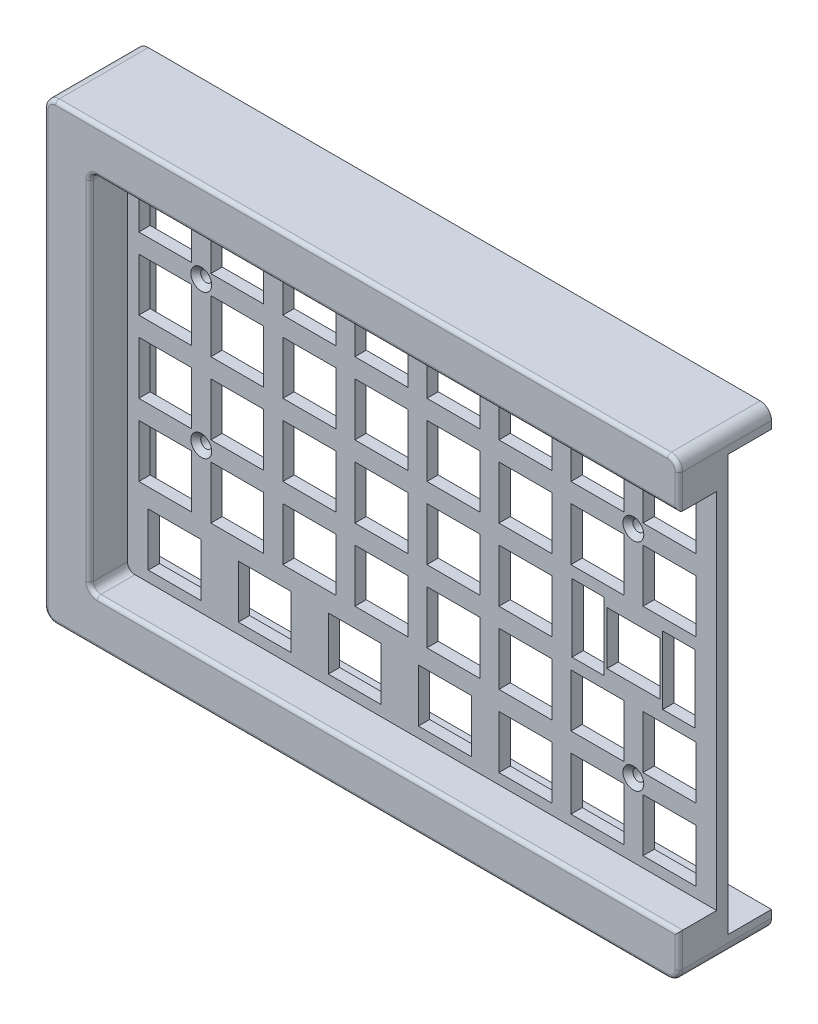
SolidWorks part; units mm, degrees
ref_plane "Front Plane" through (0, 0, 0) normal (0, 0, 1) x (1, 0, 0)
ref_plane "Top Plane" through (0, 0, 0) normal (0, 1, 0) x (1, 0, 0)
ref_plane "Right Plane" through (0, 0, 0) normal (1, 0, 0) x (0, 0, -1)
sketch "Sketch1" plane through (0, 0, 0) normal (0, 0, 1) x (1, 0, 0)
  line L1 (-80.925, -60) -> (80.925, -60)
  line L2 (-83.925, -57) -> (-83.925, 57)
  line L3 (-80.925, 60) -> (80.925, 60)
  line L4 (83.925, -57) -> (83.925, 57)
  line L5 (-83.925, -60) -> (83.925, 60) construction
  line L6 (-83.925, 60) -> (83.925, -60) construction
  arc A0 (80.925, -60) -> (83.925, -57) centre (80.925, -57) ccw
  arc A1 (80.925, 60) -> (83.925, 57) centre (80.925, 57) cw
  arc A2 (-83.925, 57) -> (-80.925, 60) centre (-80.925, 57) cw
  arc A3 (-80.925, -60) -> (-83.925, -57) centre (-80.925, -57) cw
  point P0 (0, 0)
  dimension "D3" = 3
  dimension "D1" = 167.85
  dimension "D2" = 120
extrude "Main Extrusion" add sketch "Sketch1" along normal blind 24.5
sketch "Sketch3" plane through (0, 0, 24.5) normal (0, 0, 1) x (1, 0, 0)
  line L0 (-83.925, 57) -> (-83.925, -57) construction
  line L1 (-69.925, 48) -> (82.025, 48)
  line L2 (-71.925, 46) -> (-71.925, -46)
  line L3 (-69.925, -48) -> (82.025, -48)
  line L4 (83.925, 46) -> (83.925, -46)
  line L5 (-71.925, 48) -> (83.925, -48) construction
  line L6 (-71.925, -48) -> (83.925, 48) construction
  line L7 (-80.925, -60) -> (80.925, -60) construction
  line L8 (83.925, -46) -> (83.925, -48)
  line L9 (80.925, 60) -> (-80.925, 60) construction
  line L10 (83.925, -48) -> (82.025, -48)
  line L11 (83.925, -57) -> (83.925, 57) construction
  line L12 (82.025, 48) -> (83.925, 48)
  line L13 (83.925, 48) -> (83.925, 46)
  arc A2 (-71.925, -46) -> (-69.925, -48) centre (-69.925, -46) ccw
  arc A3 (-69.925, 48) -> (-71.925, 46) centre (-69.925, 46) ccw
  point P0 (6, 0)
  dimension "D6" = 2
  dimension "D1" = 12
  dimension "D2" = 0
  dimension "D3" = 12
  dimension "D4" = 12
extrude "Front Cave" cut sketch "Sketch3" against normal blind 10
sketch "Sketch2" plane through (0, 0, 14.5) normal (0, 0, 1) x (1, 0, 0)
  line L1 (-68.925, 31) -> (-54.925, 31)
  line L2 (-68.925, 31) -> (-68.925, 45)
  line L3 (-68.925, 45) -> (-54.925, 45)
  line L4 (-54.925, 31) -> (-54.925, 45)
  line L5 (-68.925, 31) -> (-54.925, 45) construction
  line L6 (-68.925, 45) -> (-54.925, 31) construction
  line L7 (-49.875, 31) -> (-49.875, 45)
  line L8 (-49.875, 31) -> (-35.875, 31)
  line L9 (-35.875, 31) -> (-35.875, 45)
  line L10 (-49.875, 45) -> (-35.875, 45)
  line L11 (-30.825, 31) -> (-30.825, 45)
  line L12 (-30.825, 31) -> (-16.825, 31)
  line L13 (-16.825, 31) -> (-16.825, 45)
  line L14 (-30.825, 45) -> (-16.825, 45)
  line L15 (-11.775, 31) -> (-11.775, 45)
  line L16 (-11.775, 31) -> (2.225, 31)
  line L17 (2.225, 31) -> (2.225, 45)
  line L18 (-11.775, 45) -> (2.225, 45)
  line L19 (7.275, 31) -> (7.275, 45)
  line L20 (7.275, 31) -> (21.275, 31)
  line L21 (21.275, 31) -> (21.275, 45)
  line L22 (7.275, 45) -> (21.275, 45)
  line L23 (26.325, 31) -> (26.325, 45)
  line L24 (26.325, 31) -> (40.325, 31)
  line L25 (40.325, 31) -> (40.325, 45)
  line L26 (26.325, 45) -> (40.325, 45)
  line L27 (45.375, 31) -> (45.375, 45)
  line L28 (45.375, 31) -> (59.375, 31)
  line L100 (-42.613, -31.2) -> (-42.613, -45.2)
  line L101 (-66.425, -31.2) -> (-52.425, -31.2)
  line L102 (-66.425, -31.2) -> (-66.425, -45.2)
  line L103 (-66.425, -45.2) -> (-52.425, -45.2)
  line L104 (-52.425, -31.2) -> (-52.425, -45.2)
  line L105 (-66.425, -31.2) -> (-52.425, -45.2) construction
  line L106 (-66.425, -45.2) -> (-52.425, -31.2) construction
  line L107 (-42.613, -31.2) -> (-28.613, -31.2)
  line L108 (-28.613, -31.2) -> (-28.613, -45.2)
  line L109 (-42.613, -45.2) -> (-28.613, -45.2)
  line L110 (-18.801, -31.2) -> (-18.801, -45.2)
  line L111 (-18.801, -31.2) -> (-4.801, -31.2)
  line L112 (-4.801, -31.2) -> (-4.801, -45.2)
  line L113 (-18.801, -45.2) -> (-4.801, -45.2)
  line L119 (5.011, -31.2) -> (5.011, -45.2)
  line L120 (5.011, -31.2) -> (19.011, -31.2)
  line L125 (80.925, 60) -> (-80.925, 60) construction
  line L126 (-83.925, 57) -> (-83.925, -57) construction
  line L127 (59.375, 31) -> (59.375, 45)
  line L132 (19.011, -31.2) -> (19.011, -45.2)
  line L133 (5.011, -45.2) -> (19.011, -45.2)
  line L134 (69.65, -9.1) -> (78.15, -9.1)
  line L135 (69.65, -9.1) -> (69.65, 8.9)
  line L136 (69.65, 8.9) -> (78.15, 8.9)
  line L137 (78.15, -9.1) -> (78.15, 8.9)
  line L138 (69.65, -9.1) -> (78.15, 8.9) construction
  line L139 (69.65, 8.9) -> (78.15, -9.1) construction
  line L140 (45.375, 45) -> (59.375, 45)
  line L141 (64.425, 31) -> (64.425, 45)
  line L142 (64.425, 31) -> (78.425, 31)
  line L143 (78.425, 31) -> (78.425, 45)
  line L144 (64.425, 45) -> (78.425, 45)
  line L145 (-68.925, 11.95) -> (-68.925, 25.95)
  line L146 (-68.925, 11.95) -> (-54.925, 11.95)
  line L147 (-54.925, 11.95) -> (-54.925, 25.95)
  line L148 (-68.925, 25.95) -> (-54.925, 25.95)
  line L149 (-49.875, 11.95) -> (-49.875, 25.95)
  line L150 (-49.875, 25.95) -> (-35.875, 25.95)
  line L151 (-35.875, 11.95) -> (-35.875, 25.95)
  line L152 (-49.875, 11.95) -> (-35.875, 11.95)
  line L153 (-30.825, 11.95) -> (-30.825, 25.95)
  line L154 (-30.825, 25.95) -> (-16.825, 25.95)
  line L155 (-16.825, 11.95) -> (-16.825, 25.95)
  line L156 (-30.825, 11.95) -> (-16.825, 11.95)
  line L157 (-11.775, 11.95) -> (-11.775, 25.95)
  line L158 (-11.775, 25.95) -> (2.225, 25.95)
  line L159 (2.225, 11.95) -> (2.225, 25.95)
  line L160 (-11.775, 11.95) -> (2.225, 11.95)
  line L161 (7.275, 11.95) -> (7.275, 25.95)
  line L162 (7.275, 25.95) -> (21.275, 25.95)
  line L163 (21.275, 11.95) -> (21.275, 25.95)
  line L164 (7.275, 11.95) -> (21.275, 11.95)
  line L165 (26.325, 11.95) -> (26.325, 25.95)
  line L166 (26.325, 25.95) -> (40.325, 25.95)
  line L167 (40.325, 11.95) -> (40.325, 25.95)
  line L168 (26.325, 11.95) -> (40.325, 11.95)
  line L169 (45.375, 11.95) -> (45.375, 25.95)
  line L170 (45.375, 25.95) -> (59.375, 25.95)
  line L171 (59.375, 11.95) -> (59.375, 25.95)
  line L172 (45.375, 11.95) -> (59.375, 11.95)
  line L173 (64.425, 11.95) -> (64.425, 25.95)
  line L174 (64.425, 25.95) -> (78.425, 25.95)
  line L175 (78.425, 11.95) -> (78.425, 25.95)
  line L176 (64.425, 11.95) -> (78.425, 11.95)
  line L177 (-68.925, -7.1) -> (-68.925, 6.9)
  line L178 (-68.925, -7.1) -> (-54.925, -7.1)
  line L179 (-54.925, -7.1) -> (-54.925, 6.9)
  line L180 (-68.925, 6.9) -> (-54.925, 6.9)
  line L181 (-49.875, -7.1) -> (-49.875, 6.9)
  line L182 (-49.875, 6.9) -> (-35.875, 6.9)
  line L183 (-35.875, -7.1) -> (-35.875, 6.9)
  line L184 (-49.875, -7.1) -> (-35.875, -7.1)
  line L185 (-30.825, -7.1) -> (-30.825, 6.9)
  line L186 (-30.825, 6.9) -> (-16.825, 6.9)
  line L187 (-16.825, -7.1) -> (-16.825, 6.9)
  line L188 (-30.825, -7.1) -> (-16.825, -7.1)
  line L189 (-11.775, -7.1) -> (-11.775, 6.9)
  line L190 (-11.775, 6.9) -> (2.225, 6.9)
  line L191 (2.225, -7.1) -> (2.225, 6.9)
  line L192 (-11.775, -7.1) -> (2.225, -7.1)
  line L193 (7.275, -7.1) -> (7.275, 6.9)
  line L194 (7.275, 6.9) -> (21.275, 6.9)
  line L195 (21.275, -7.1) -> (21.275, 6.9)
  line L196 (7.275, -7.1) -> (21.275, -7.1)
  line L197 (26.325, -7.1) -> (26.325, 6.9)
  line L198 (26.325, 6.9) -> (40.325, 6.9)
  line L199 (40.325, -7.1) -> (40.325, 6.9)
  line L200 (26.325, -7.1) -> (40.325, -7.1)
  line L209 (-68.925, -26.15) -> (-68.925, -12.15)
  line L210 (-68.925, -26.15) -> (-54.925, -26.15)
  line L211 (-54.925, -26.15) -> (-54.925, -12.15)
  line L212 (-68.925, -12.15) -> (-54.925, -12.15)
  line L213 (-49.875, -26.15) -> (-49.875, -12.15)
  line L214 (-49.875, -12.15) -> (-35.875, -12.15)
  line L215 (-35.875, -26.15) -> (-35.875, -12.15)
  line L216 (-49.875, -26.15) -> (-35.875, -26.15)
  line L217 (-30.825, -26.15) -> (-30.825, -12.15)
  line L218 (-30.825, -12.15) -> (-16.825, -12.15)
  line L219 (-16.825, -26.15) -> (-16.825, -12.15)
  line L220 (-30.825, -26.15) -> (-16.825, -26.15)
  line L221 (-11.775, -26.15) -> (-11.775, -12.15)
  line L222 (-11.775, -12.15) -> (2.225, -12.15)
  line L223 (2.225, -26.15) -> (2.225, -12.15)
  line L224 (-11.775, -26.15) -> (2.225, -26.15)
  line L225 (7.275, -26.15) -> (7.275, -12.15)
  line L226 (7.275, -12.15) -> (21.275, -12.15)
  line L227 (21.275, -26.15) -> (21.275, -12.15)
  line L228 (7.275, -26.15) -> (21.275, -26.15)
  line L229 (26.325, -26.15) -> (26.325, -12.15)
  line L230 (26.325, -12.15) -> (40.325, -12.15)
  line L231 (40.325, -26.15) -> (40.325, -12.15)
  line L232 (26.325, -26.15) -> (40.325, -26.15)
  line L233 (45.375, -26.15) -> (45.375, -12.15)
  line L234 (45.375, -12.15) -> (59.375, -12.15)
  line L235 (59.375, -26.15) -> (59.375, -12.15)
  line L236 (45.375, -26.15) -> (59.375, -26.15)
  line L237 (64.425, -26.15) -> (64.425, -12.15)
  line L238 (64.425, -12.15) -> (78.425, -12.15)
  line L239 (78.425, -26.15) -> (78.425, -12.15)
  line L240 (64.425, -26.15) -> (78.425, -26.15)
  line L241 (45.375, -7.1) -> (45.375, 6.9) [skipped]
  line L242 (45.375, 6.9) -> (59.375, 6.9) [skipped]
  line L243 (59.375, -7.1) -> (59.375, 6.9) [skipped]
  line L244 (45.375, -7.1) -> (59.375, -7.1) [skipped]
  line L245 (64.425, -7.1) -> (64.425, 6.9) [skipped]
  line L246 (64.425, 6.9) -> (78.425, 6.9) [skipped]
  line L247 (78.425, -7.1) -> (78.425, 6.9) [skipped]
  line L248 (64.425, -7.1) -> (78.425, -7.1) [skipped]
  line L249 (61.9, 6.9) -> (61.9, -7.1) construction
  line L250 (54.9, -7.1) -> (68.9, -7.1)
  line L251 (54.9, -7.1) -> (54.9, 6.9)
  line L252 (54.9, 6.9) -> (68.9, 6.9)
  line L253 (68.9, -7.1) -> (68.9, 6.9)
  line L254 (54.9, -7.1) -> (68.9, 6.9) construction
  line L255 (54.9, 6.9) -> (68.9, -7.1) construction
  line L256 (54.15, 8.9) -> (45.65, 8.9)
  line L257 (45.65, -9.1) -> (45.65, 8.9)
  line L258 (54.15, -9.1) -> (45.65, -9.1)
  line L259 (54.15, -9.1) -> (54.15, 8.9)
  line L260 (26.325, -45.2) -> (26.325, -31.2)
  line L261 (26.325, -31.2) -> (40.325, -31.2)
  line L262 (40.325, -45.2) -> (40.325, -31.2)
  line L263 (26.325, -45.2) -> (40.325, -45.2)
  line L264 (45.375, -45.2) -> (45.375, -31.2)
  line L265 (45.375, -31.2) -> (59.375, -31.2)
  line L266 (59.375, -45.2) -> (59.375, -31.2)
  line L267 (45.375, -45.2) -> (59.375, -45.2)
  line L268 (64.425, -45.2) -> (64.425, -31.2)
  line L269 (64.425, -31.2) -> (78.425, -31.2)
  line L270 (78.425, -45.2) -> (78.425, -31.2)
  line L271 (64.425, -45.2) -> (78.425, -45.2)
  line L273 (83.925, -48) -> (83.925, 48) construction
  point P0 (-61.925, 38)
  point P29 (-59.425, -38.2)
  point P30 (61.9, -0.1)
  point P141 (73.9, -0.1)
  dimension "D22" = 5.05
  dimension "D1" = 14
  dimension "D2" = 14
  dimension "D3" = 8
  dimension "D5" = 15
  dimension "D6" = 5.05
  dimension "D7" = 4
  dimension "D8" = 5.05
  dimension "D10" = 14
  dimension "D11" = 14
  dimension "D12" = 14
  dimension "D13" = 5.5
  dimension "D14" = 14
  dimension "D16" = 9.812
  dimension "D17" = 5.05
  dimension "D18" = 2
  dimension "D19" = 5.05
  dimension "D20" = 14.575
  dimension "D21" = 17.5
  dimension "D23" = 12
  dimension "D44" = 8.5
  dimension "D45" = 18
  dimension "D9" = 3
  dimension "D15" = 4
extrude "Key Cutouts" cut sketch "Sketch2" against normal blind 3
hole_wizard "CSK for M2.5 Countersunk Flat Head Screw1" positions "3DSketch1" profile "Sketch5" countersink size "M2.5" standard "ISO" end condition through all
sketch3d "3DSketch1"
  line L2 (-68.925, 31, 14.5) -> (-54.925, 31, 14.5) construction
  line L9 (-49.875, 25.95, 14.5) -> (-49.875, 11.95, 14.5) construction
  line L14 (59.375, -31.2, 14.5) -> (45.375, -31.2, 14.5) construction
  line L15 (64.425, -31.2, 14.5) -> (64.425, -45.2, 14.5) construction
  line L16 (-54.925, -7.1, 14.5) -> (-54.925, 6.9, 14.5) construction
  line L17 (-49.875, -7.1, 14.5) -> (-35.875, -7.1, 14.5) construction
  line L18 (64.425, 31, 14.5) -> (78.425, 31, 14.5) construction
  line L19 (64.425, 25.95, 14.5) -> (64.425, 11.95, 14.5) construction
  point P0 (-52.4, 28.475, 14.5)
  point P4 (61.895, -28.67, 14.5)
  point P6 (-52.4, -9.625, 14.5)
  point P64 (61.895, 28.47, 14.5)
  dimension "D1" = 2.525
  dimension "D2" = 2.525
  dimension "D3" = 2.525
  dimension "D4" = 2.525
  dimension "D5" = 2.53
  dimension "D6" = 2.53
  dimension "D7" = 2.53
  dimension "D8" = 2.53
sketch "Sketch5" plane through (-52.4, 28.475, 14.5) normal (1, 0, 0) x (0, -1, 0)
  line L0 (0, 0) -> (0, 14.5)
  line L1 (0, 14.5) -> (1.45, 14.5)
  line L2 (1.45, 14.5) -> (1.45, 1.3)
  line L3 (1.45, 1.3) -> (2.75, 0)
  line L5 (2.75, 0) -> (0, 0)
  line L6 (-1.45, 1.3) -> (-2.75, 0) construction
  line L11 (0, -6.35) -> (0, 107.95) construction
  dimension "Thru Hole Dia." = 2.9
  dimension "Thru Hole Depth" = 14.5
  dimension "Near C'Sink Dia." = 5.5
  dimension "Near C'Sink Angle" = 90
sketch "Sketch4" plane through (0, 0, 0) normal (0, 0, 1) x (1, 0, 0)
  line L5 (83.925, -57) -> (83.925, 57) construction
  line L6 (83.925, 55) -> (-78.925, 55)
  line L12 (83.925, 55) -> (83.925, -55)
  line L13 (83.925, -55) -> (-78.925, -55)
  line L14 (-78.925, 55) -> (-78.925, -55)
  line L15 (80.925, 60) -> (-80.925, 60) construction
  line L16 (-80.925, -60) -> (80.925, -60) construction
  line L17 (-83.925, 57) -> (-83.925, -57) construction
  dimension "D1" = 5
  dimension "D2" = 5
  dimension "D3" = 5
extrude "Cut-Extrude1" cut sketch "Sketch4" along normal up to surface (11.5 mm away) contours L14 L13 L12 L6 up to face at (-61.925, 18.95, 11.5)
sketch "Sketch7" plane through (-83.925, 0, 0) normal (-1, 0, 0) x (0, 0, 1)
  line L0 (0, 40) -> (7, 32)
  line L1 (0, 57) -> (0, -57) construction
  line L2 (7, 32) -> (7, -60)
  line L3 (7, -60) -> (0, -60)
  line L4 (0, -60) -> (0, 40)
  line L5 (24.5, 57) -> (0, 57) construction
  line L7 (24.5, -60) -> (0, -60) construction
  dimension "D1" = 17
  dimension "D2" = 25
  dimension "D5" = 7
sketch "Sketch8" plane through (0, -60, 0) normal (0, -1, 0) x (1, 0, 0)
  line L0 (-83.925, 0) -> (-83.925, 7)
  line L1 (-80.925, 0) -> (80.925, 0) construction
  line L2 (-83.925, 7) -> (55.925, 7)
  line L3 (55.925, 7) -> (63.925, 0)
  line L4 (63.925, 0) -> (-83.925, 0)
  line L6 (80.925, 24.5) -> (80.925, 0) construction
  line L7 (-83.925, 24.5) -> (-83.925, 0) construction
  dimension "D3" = 17
  dimension "D4" = 25
  dimension "D5" = 7
extrude "Cut-Extrude3" cut sketch "Sketch7" against normal blind 2.5
extrude "Cut-Extrude4" cut sketch "Sketch8" against normal blind 2.5
fillet "Fillet1" radius 1 15 edges at (-83.925, 0, 24.5) (-83.0463, 59.1213, 24.5) (0, 60, 24.5) (83.0463, 59.1213, 24.5) (83.925, 52.5, 24.5) (83.925, -52.5, 24.5) (83.0463, -59.1213, 24.5) (0, -60, 24.5) (-83.0463, -59.1213, 24.5) (7, -48, 24.5) (7, 48, 24.5) (-71.3392, 47.4142, 24.5) (-71.925, 0, 24.5) (-71.3392, -47.4142, 24.5) (-81.425, -57.5, 3.5)
sketch "Sketch10" plane through (0, 0, 11.5) normal (0, 0, -1) x (-1, 0, 0)
  line L1 (75.725, 5) -> (78.925, 5)
  line L2 (75.725, 5) -> (75.725, -55)
  line L3 (75.725, -55) -> (78.925, -55)
  line L4 (78.925, 5) -> (78.925, -55)
  line L6 (78.925, 55) -> (78.925, -55) construction
  line L7 (-83.925, -55) -> (78.925, -55) construction
  point P10 (0, 0)
  point P11 (0, 0)
  dimension "D1" = 60
  dimension "D2" = 3.2
extrude "Cut-Extrude5" cut sketch "Sketch10" against normal blind 8
